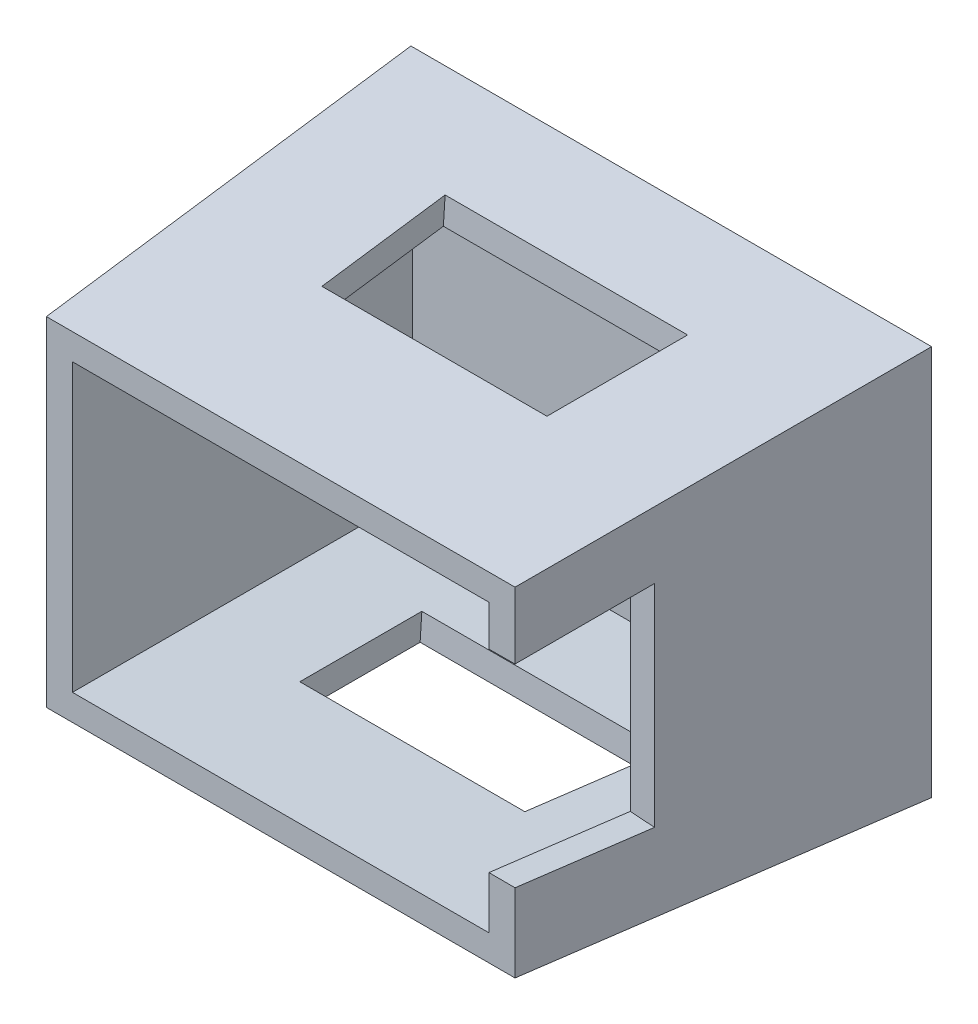
SolidWorks part; units mm, degrees
ref_plane "前视基准面" through (0, 0, 0) normal (0, 0, 1) x (1, 0, 0)
ref_plane "上视基准面" through (0, 0, 0) normal (0, 1, 0) x (1, 0, 0)
ref_plane "右视基准面" through (0, 0, 0) normal (1, 0, 0) x (0, 0, -1)
sketch "草图1" plane through (0, 0, 0) normal (0, 0, 1) x (1, 0, 0)
  line L1 (-20, 15) -> (20, 15)
  line L2 (-20, 15) -> (-20, -15)
  line L3 (-20, -15) -> (20, -15)
  line L4 (20, 15) -> (20, -15)
  line L5 (-20, 15) -> (20, -15) construction
  line L6 (-20, -15) -> (20, 15) construction
  point P0 (0, 0)
  dimension "D1" = 40
  dimension "D2" = 30
ref_plane "基准面4" through (0, 0, 30) normal (0, 0, 1) x (1, 0, 0)
sketch "草图2" plane through (0, 0, 30) normal (0, 0, 1) x (1, 0, 0)
  line L14 (18, -13) -> (18, 13)
  line L15 (-18, -13) -> (18, -13)
  line L16 (-18, 13) -> (-18, -13)
  line L17 (18, 13) -> (-18, 13)
  line L18 (18, -13) -> (18, 13)
  line L19 (-18, -13) -> (18, -13)
  line L20 (-18, 13) -> (-18, -13)
  line L21 (18, 13) -> (-18, 13)
  dimension "D1" = 2
loft "放样1" add profiles "草图2", "草图1"
shell "抽壳1" thickness 2
sketch "草图3" plane through (0, -14.9336, 0.9956) normal (0, -0.9978, 0.0665) x (1, 0, 0)
  line L8 (-19.8714, 31.0688) -> (-22.1375, -2.9978)
  line L9 (-22.1375, -2.9978) -> (22.1375, -2.9978)
  line L10 (22.1375, -2.9978) -> (19.8714, 31.0688)
  line L11 (19.8714, 31.0688) -> (-19.8714, 31.0688)
  line L12 (-19.8714, 31.0688) -> (-22.1375, -2.9978)
  line L13 (-22.1375, -2.9978) -> (22.1375, -2.9978)
  line L14 (22.1375, -2.9978) -> (19.8714, 31.0688)
  line L15 (19.8714, 31.0688) -> (-19.8714, 31.0688)
  line L20 (-18, 29.0688) -> (-20, -0.9978)
  line L21 (-20, -0.9978) -> (20, -0.9978)
  line L22 (20, -0.9978) -> (18, 29.0688)
  line L23 (18, 29.0688) -> (-18, 29.0688)
  line L24 (-10.5145, 21.0688) -> (-11.4502, 7.0022)
  line L25 (-11.4502, 7.0022) -> (11.4502, 7.0022)
  line L26 (11.4502, 7.0022) -> (10.5145, 21.0688)
  line L27 (10.5145, 21.0688) -> (-10.5145, 21.0688)
  line L28 (-8.6431, 19.0688) -> (-9.3127, 9.0022)
  line L29 (-9.3127, 9.0022) -> (9.3127, 9.0022)
  line L30 (9.3127, 9.0022) -> (8.6431, 19.0688)
  line L31 (8.6431, 19.0688) -> (-8.6431, 19.0688)
  dimension "D1" = 2
  dimension "D2" = 2
  dimension "D3" = 10
extrude "切除-拉伸1" cut sketch "草图3" against normal through all contours L30 L31 L28 L29
sketch "草图4" plane through (19.9115, 0, 1.3274) normal (0.9978, 0, 0.0665) x (0.0665, 0, -0.9978)
  line L12 (-31.2409, -6.8315) -> (-18.6696, -7.6677)
  line L13 (-18.6696, -7.6677) -> (-18.6696, 8.5563)
  line L14 (-18.6696, 8.5563) -> (-31.2409, 7.7201)
  line L15 (-31.2409, 7.7201) -> (-31.2409, -6.8315)
extrude "切除-拉伸4" cut sketch "草图4" against normal blind 10
